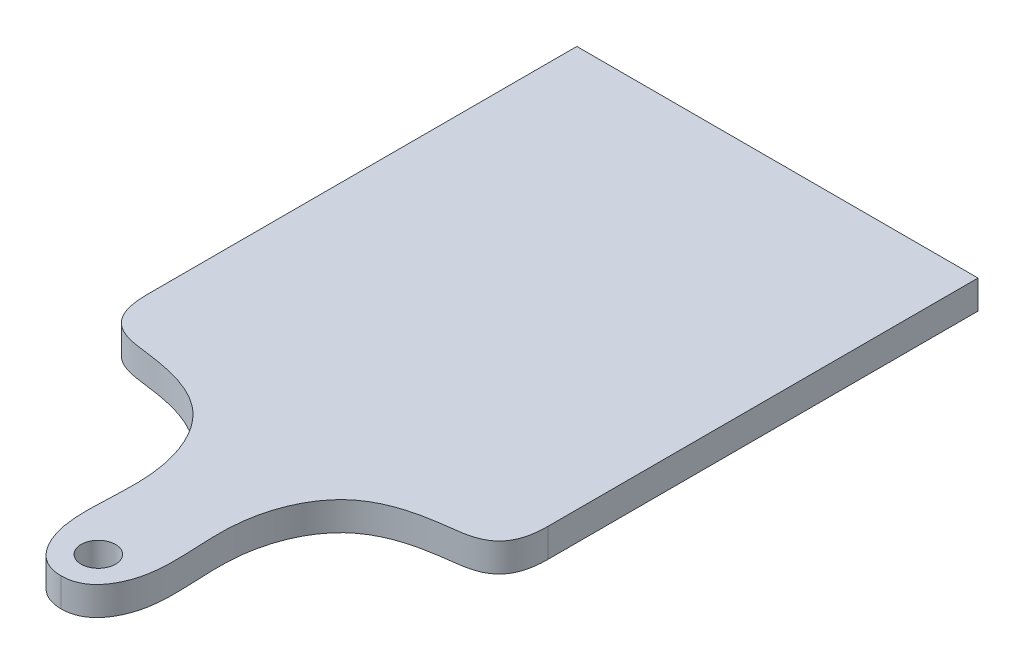
SolidWorks part; units mm, degrees
ref_plane "Płaszczyzna przednia" through (0, 0, 0) normal (0, 0, 1) x (1, 0, 0)
ref_plane "Płaszczyzna górna" through (0, 0, 0) normal (0, 1, 0) x (1, 0, 0)
ref_plane "Płaszczyzna prawa" through (0, 0, 0) normal (1, 0, 0) x (0, 0, -1)
sketch "Szkic1" plane through (0, 0, 0) normal (0, 1, 0) x (1, 0, 0)
  line L0 (0, 100) -> (0, 0) construction
  line L1 (0, 0) -> (0, -150) construction
  line L2 (-70, 100) -> (70, 100)
  line L3 (-70, 100) -> (-70, -50)
  line L4 (70, 100) -> (70, -50)
  circle A5 centre (0, -137) radius 6
  spline S0 degree 3 poles (70, -50) (70, -66.8366) (50.0968, -66.5068) (23.1664, -74.7071) (10.7875, -106.8967) (19.2784, -136.0814) (6.2284, -150) (0, -150) knots 0 0 0 0 0.201262 0.386001 0.607005 0.892124 1 1 1 1
  spline S1 degree 3 poles (-70, -50) (-70, -66.8366) (-50.0968, -66.5068) (-23.1664, -74.7071) (-10.7875, -106.8967) (-19.2784, -136.0814) (-6.2284, -150) (0, -150) knots 0 0 0 0 0.201262 0.386001 0.607005 0.892124 1 1 1 1
  dimension "D3" = 12
  dimension "D14" = 100
  dimension "D1" = 140
  dimension "D2" = 250
  dimension "D4" = 100
  dimension "D5" = 82
  dimension "D6" = 73
  dimension "D7" = 46
  dimension "D8" = 8
  dimension "D9" = 100
  dimension "D10" = 54
  dimension "D11" = 30
  dimension "D12" = 24
  dimension "D13" = 13
extrude "Dodanie-wyciągnięcie1" add sketch "Szkic1" along normal blind 10
